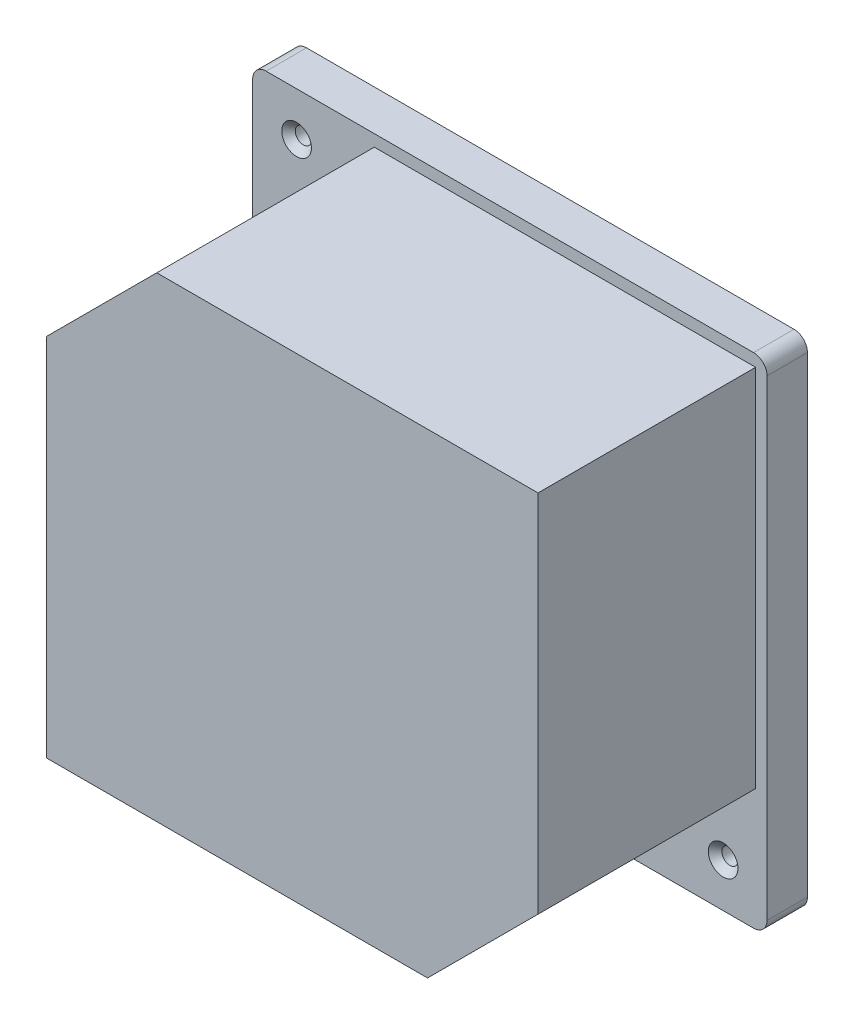
SolidWorks part; units mm, degrees
ref_plane "Front Plane" through (0, 0, 0) normal (0, 0, 1) x (1, 0, 0)
ref_plane "Top Plane" through (0, 0, 0) normal (0, 1, 0) x (1, 0, 0)
ref_plane "Right Plane" through (0, 0, 0) normal (1, 0, 0) x (0, 0, -1)
sketch "Sketch1" plane through (0, 0, 0) normal (0, 0, 1) x (1, 0, 0)
  line L1 (-14.3268, 27.6732) -> (42.0732, 27.6732)
  line L2 (-30.8868, 11.5066) -> (-30.8868, -42.8868)
  line L3 (-30.8868, -42.8868) -> (25.5132, -42.8868)
  line L4 (42.0732, 27.6732) -> (42.0732, -26.7201)
  line L5 (-30.8868, 27.6732) -> (-30.8868, 11.5066) construction
  line L6 (-30.8868, 27.6732) -> (-14.3268, 27.6732) construction
  line L16 (25.5132, -42.8868) -> (42.0732, -42.8868) construction
  line L17 (42.0732, -42.8868) -> (42.0732, -26.7201) construction
  line L18 (-32.5868, 29.4132) -> (-32.5868, -44.5868)
  line L19 (-32.5868, -44.5868) -> (43.7732, -44.5868)
  line L20 (43.7732, -44.5868) -> (43.7732, 29.4132)
  line L21 (43.7732, 29.4132) -> (-32.5868, 29.4132)
  line L22 (-28.7868, 13.4132) -> (-16.5868, 25.6132)
  line L23 (-16.5868, 25.6132) -> (27.7754, 25.6132)
  line L24 (27.7754, 25.6132) -> (39.9754, 13.4132)
  line L25 (39.9754, 13.4132) -> (39.9754, -28.5868)
  line L26 (39.9754, -28.5868) -> (27.7754, -40.7868)
  line L27 (27.7754, -40.7868) -> (-16.5868, -40.7868)
  line L28 (-16.5868, -40.7868) -> (-28.7868, -28.5868)
  line L29 (-28.7868, -28.5868) -> (-28.7868, 13.4132)
  point P0 (0, 0)
  point P17 (37.1932, -38.3041)
  point P18 (-26.3113, 22.7932)
  dimension "D1" = 56.4
  dimension "D2" = 70.56
  dimension "D3" = 56.4
  dimension "D4" = 4.88
  dimension "D6" = 1.7
  dimension "D7" = 74
  dimension "D8" = 1.7
  dimension "D9" = 1.7
  dimension "D11" = 76.36
  dimension "D12" = 4.88
extrude "Boss-Extrude1" add sketch "Sketch1" along normal blind 6
sketch "Sketch2" plane through (0, 0, 0) normal (0, 0, 1) x (1, 0, 0)
  line L15 (39.9754, -28.5868) -> (27.7754, -40.7868) construction
  line L16 (42.0732, 27.6732) -> (42.0732, -26.4889)
  line L17 (27.7754, -40.7868) -> (25.6754, -42.8868) construction
  line L18 (25.6754, -42.8868) -> (42.0732, -26.4889) construction
  line L19 (-28.7868, 13.4132) -> (-16.5868, 25.6132) construction
  line L20 (25.5132, -42.8868) -> (42.0732, -42.8868) construction
  line L21 (25.6754, -42.8868) -> (-30.8868, -42.8868)
  line L22 (-16.5868, 25.6132) -> (-14.5268, 27.6732) construction
  line L25 (-30.8868, 27.6732) -> (-14.3268, 27.6732) construction
  line L26 (-14.5268, 27.6732) -> (-30.8868, 11.3132) construction
  line L28 (-30.8868, 11.5066) -> (-30.8868, -42.8868) construction
  line L29 (-30.8868, 11.3132) -> (-14.5268, 27.6732)
  line L30 (-14.5268, 27.6732) -> (42.0732, 27.6732)
  line L31 (42.0732, -26.4889) -> (25.6754, -42.8868)
  line L32 (25.6754, -42.8868) -> (-30.8868, -42.8868)
  line L33 (-30.8868, 11.5066) -> (-30.8868, -42.8868)
sketch "Sketch3" plane through (0, 0, 0) normal (0, 0, -1) x (-1, 0, 0)
  line L8 (-25.1686, -40.7868) -> (28.7868, -40.7868)
  line L11 (-27.7754, -40.7868) -> (16.5868, -40.7868) construction
  line L12 (28.7868, -40.7868) -> (28.7868, 10.4917)
  line L13 (28.7868, 13.4132) -> (28.7868, -28.5868) construction
  line L14 (28.7868, 10.4917) -> (13.3867, 25.6132)
  line L15 (-27.7754, 25.6132) -> (16.5868, 25.6132) construction
  line L16 (13.3867, 25.6132) -> (-39.7917, 25.6132)
  line L17 (-39.7917, 25.6132) -> (-39.9754, -26.119)
  line L18 (-39.9754, -28.5868) -> (-39.9754, 13.4132) construction
  line L19 (-39.9754, -26.119) -> (-25.1686, -40.7868)
sketch "Sketch4" plane through (0, 0, 6) normal (0, 0, 1) x (1, 0, 0)
  circle A2 centre (-26.0667, 22.8932) radius 2.2
  circle A3 centre (37.2554, -38.0667) radius 2.2
fillet "Fillet1" radius 2 1 edges at (-32.5868, 29.4132, 3)
fillet "Fillet2" radius 2 1 edges at (43.7732, 29.4132, 3)
fillet "Fillet3" radius 2 1 edges at (-32.5868, -44.5868, 3)
fillet "Fillet4" radius 2 1 edges at (43.7732, -44.5868, 3)
hole_wizard "CSK for M2 Countersunk Raised Head Screw1" positions "Sketch6" profile "Sketch7" countersink size "M2" standard "ISO" end condition through all
sketch "Sketch6" plane through (0, 0, 6) normal (0, 0, 1) x (1, 0, 0)
  point P0 (-26.0667, 22.8932)
  point P3 (37.2554, -38.0667)
sketch "Sketch7" plane through (-26.0667, 22.8932, 6) normal (1, 0, 0) x (0, -1, 0)
  line L0 (0, 0) -> (0, 6)
  line L1 (0, 6) -> (1.2, 6)
  line L2 (1.2, 6) -> (1.2, 1)
  line L3 (1.2, 1) -> (2.2, 0)
  line L5 (2.2, 0) -> (0, 0)
  line L6 (-1.2, 1) -> (-2.2, 0) construction
  line L11 (0, -6.35) -> (0, 107.95) construction
  dimension "Thru Hole Dia." = 2.4
  dimension "Thru Hole Depth" = 6
  dimension "Near C'Sink Dia." = 4.4
  dimension "Near C'Sink Angle" = 90
extrude "Boss-Extrude2" add sketch "Sketch2" along normal blind 38.3 contours L29 L33 L21 L31 L16 L30
extrude "Cut-Extrude1" cut sketch "Sketch3" against normal blind 36.3
sketch "Sketch8" plane through (0, -42.8868, 0) normal (0, -1, 0) x (1, 0, 0)
  line L1 (-24.95, 32.8) -> (12.95, 32.8)
  line L2 (-24.95, 32.8) -> (-24.95, 11.2)
  line L3 (-24.95, 11.2) -> (12.95, 11.2)
  line L4 (12.95, 32.8) -> (12.95, 11.2)
  line L5 (-24.95, 32.8) -> (12.95, 11.2) construction
  line L6 (-24.95, 11.2) -> (12.95, 32.8) construction
  point P0 (-6, 22)
  point P5 (-6.2591, 22.3863)
  dimension "D1" = 37.9
  dimension "D2" = 21.6
extrude "Cut-Extrude2" cut sketch "Sketch8" against normal blind 10
